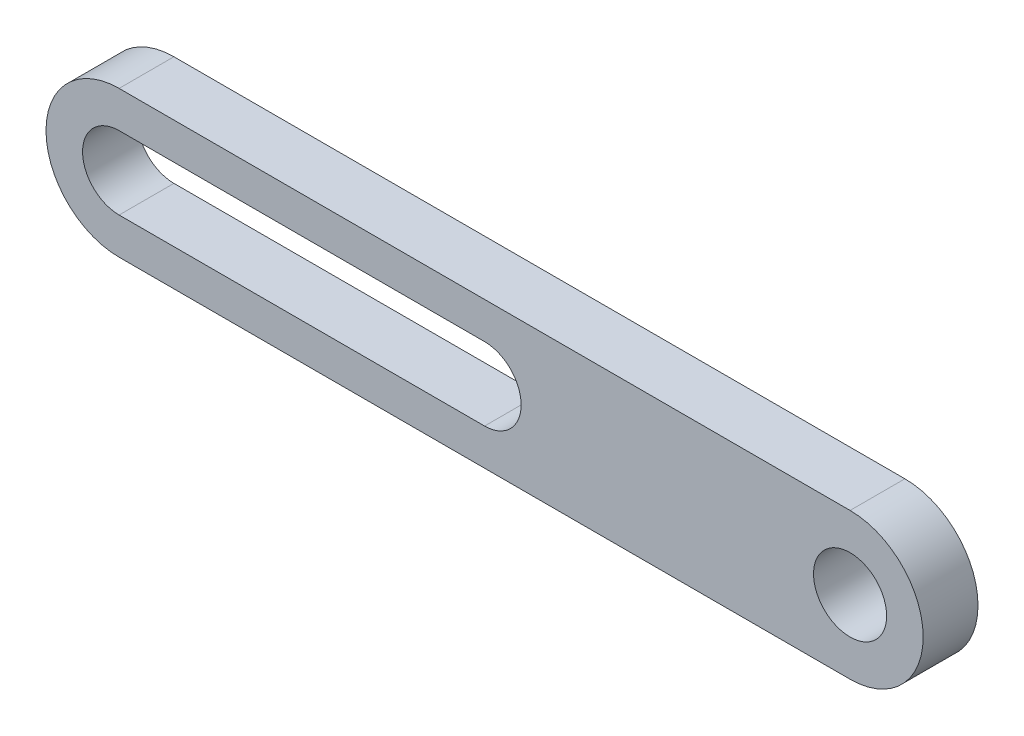
SolidWorks part; units mm, degrees
ref_plane "Front Plane" through (0, 0, 0) normal (0, 0, 1) x (1, 0, 0)
ref_plane "Top Plane" through (0, 0, 0) normal (0, 1, 0) x (1, 0, 0)
ref_plane "Right Plane" through (0, 0, 0) normal (1, 0, 0) x (0, 0, -1)
sketch "Sketch1" plane through (0, 0, 0) normal (0, 0, 1) x (1, 0, 0)
  line L0 (-10, 0) -> (10, 0) construction
  line L1 (-10, 2) -> (10, 2)
  line L2 (-10, -2) -> (10, -2)
  line L3 (-10, 0) -> (0, 0) construction
  line L4 (-10, 1) -> (0, 1)
  line L5 (-10, -1) -> (0, -1)
  arc A0 (-10, 2) -> (-10, -2) centre (-10, 0) ccw
  arc A1 (10, -2) -> (10, 2) centre (10, 0) ccw
  circle A2 centre (10, 0) radius 1
  arc A4 (-10, 1) -> (-10, -1) centre (-10, 0) ccw
  arc A5 (0, -1) -> (0, 1) centre (0, 0) ccw
  point P2 (0, 0)
  point P12 (-5, 0)
  dimension "D3" = 2
  dimension "D1" = 20
  dimension "D2" = 4
extrude "Boss-Extrude1" add sketch "Sketch1" along normal blind 1.5
